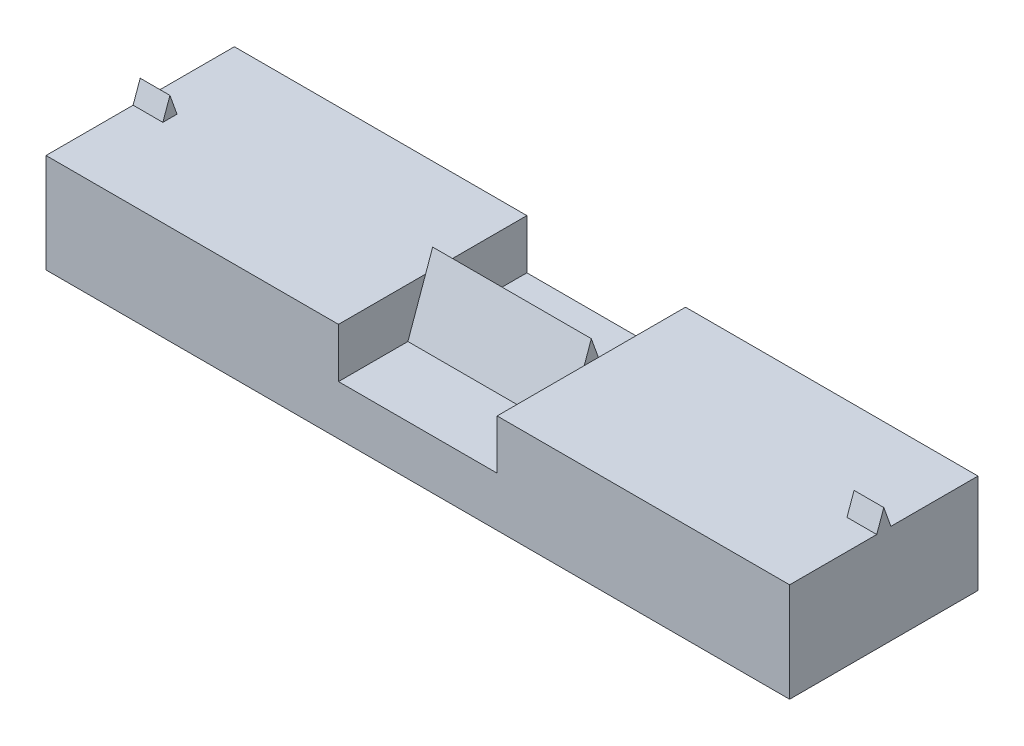
SolidWorks part; units mm, degrees
ref_plane "Front Plane" through (0, 0, 0) normal (0, 0, 1) x (1, 0, 0)
ref_plane "Top Plane" through (0, 0, 0) normal (0, 1, 0) x (1, 0, 0)
ref_plane "Right Plane" through (0, 0, 0) normal (1, 0, 0) x (0, 0, -1)
sketch "Sketch1" plane through (0, 0, 0) normal (0, 1, 0) x (1, 0, 0)
  line L1 (-37.5, -9.5) -> (37.5, -9.5)
  line L2 (-37.5, -9.5) -> (-37.5, 9.5)
  line L3 (-37.5, 9.5) -> (37.5, 9.5)
  line L4 (37.5, -9.5) -> (37.5, 9.5)
  line L5 (-37.5, -9.5) -> (37.5, 9.5) construction
  line L6 (-37.5, 9.5) -> (37.5, -9.5) construction
  point P0 (0, 0)
  dimension "D1" = 19
  dimension "D2" = 75
extrude "Boss-Extrude1" add sketch "Sketch1" against normal blind 10
sketch "Sketch4" plane through (0, 0, 0) normal (0, 1, 0) x (1, 0, 0)
  line L0 (37.5, 9.5) -> (-37.5, 9.5) construction
  line L1 (-8, -9.5) -> (8, -9.5)
  line L2 (-8, -9.5) -> (-8, 9.5)
  line L3 (-8, 9.5) -> (8, 9.5)
  line L4 (8, -9.5) -> (8, 9.5)
  line L5 (-8, -9.5) -> (8, 9.5) construction
  line L6 (-8, 9.5) -> (8, -9.5) construction
  point P0 (0, 0)
  dimension "D1" = 16
extrude "Cut-Extrude1" cut sketch "Sketch4" against normal blind 5
sketch "Sketch5" plane through (8, 0, 0) normal (-1, 0, 0) x (0, 0, 1)
  line L0 (9.5, -5) -> (-9.5, -5) construction
  line L1 (-2.5, -5) -> (0, 2)
  line L2 (0, 2) -> (2.5, -5)
  line L3 (2.5, -5) -> (-2.5, -5)
  line L4 (9.5, 0) -> (-9.5, 0) construction
  point P10 (0, 0)
  dimension "D1" = 7
  dimension "D2" = 7
  dimension "D3" = 2
extrude "Boss-Extrude2" add sketch "Sketch5" along normal blind 45.5 and the other way blind 29.5
sketch "Sketch6" plane through (0, 0, 0) normal (0, 1, 0) x (1, 0, 0)
  line L0 (-8, 9.5) -> (-37.5, 9.5) construction
  line L1 (-34.5, 9.5) -> (-8, 9.5)
  line L2 (-34.5, 9.5) -> (-34.5, -9.5)
  line L3 (-34.5, -9.5) -> (-8, -9.5)
  line L4 (-8, 9.5) -> (-8, -9.5)
  line L5 (8, -9.5) -> (37.5, -9.5) construction
  line L6 (8, 9.5) -> (34.5, 9.5)
  line L7 (8, 9.5) -> (8, -9.5)
  line L8 (8, -9.5) -> (34.5, -9.5)
  line L9 (34.5, 9.5) -> (34.5, -9.5)
  line L10 (-37.5, 9.5) -> (-37.5, 0.7143) construction
  line L11 (37.5, 0.7143) -> (37.5, 9.5) construction
  dimension "D1" = 3
  dimension "D2" = 3
extrude "Cut-Extrude2" cut sketch "Sketch6" along normal blind 2
